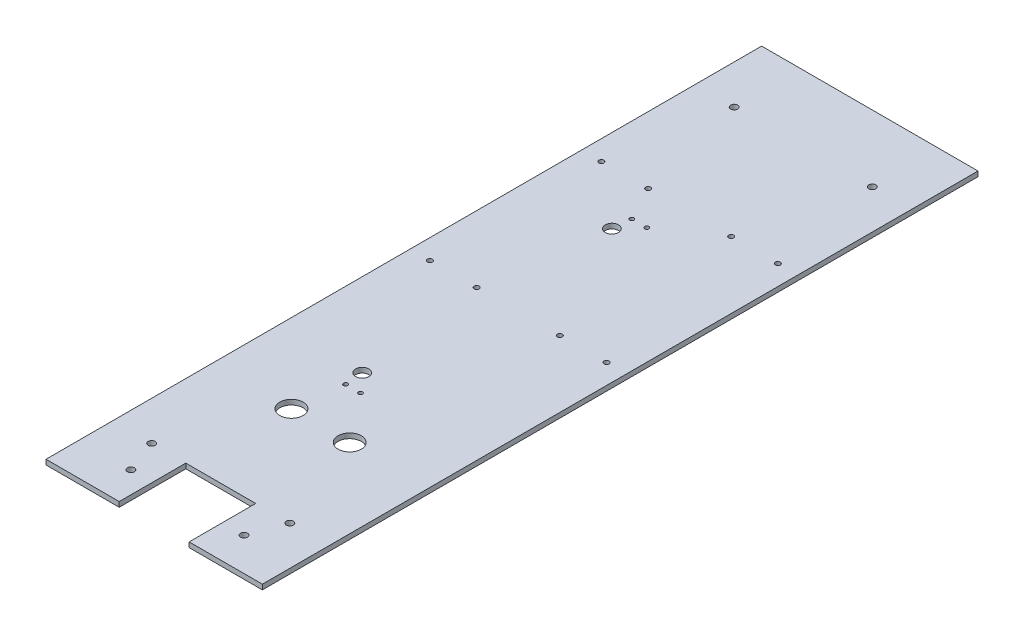
SolidWorks part; units mm, degrees
ref_plane "Front Plane" through (0, 0, 0) normal (0, 0, 1) x (1, 0, 0)
ref_plane "Top Plane" through (0, 0, 0) normal (0, 1, 0) x (1, 0, 0)
ref_plane "Right Plane" through (0, 0, 0) normal (1, 0, 0) x (0, 0, -1)
sketch "Sketch1" plane through (0, 0, 0) normal (0, 1, 0) x (1, 0, 0)
  line L1 (-65, 215) -> (65, 215)
  line L2 (-65, 215) -> (-65, -215)
  line L3 (-65, -215) -> (65, -215)
  line L4 (65, 215) -> (65, -215)
  line L5 (-65, 215) -> (65, -215) construction
  line L6 (-65, -215) -> (65, 215) construction
  point P0 (0, 0)
  dimension "D1" = 130
  dimension "D2" = 430
extrude "Boss-Extrude1" add sketch "Sketch1" along normal blind 3
sketch "Sketch2" plane through (0, 3, 0) normal (0, 1, 0) x (1, 0, 0)
  line L0 (-65, -215) -> (65, -215) construction
  line L1 (21, -215) -> (-21, -215)
  line L2 (21, -215) -> (21, -175)
  line L3 (21, -175) -> (-21, -175)
  line L4 (-21, -215) -> (-21, -175)
  line L5 (33, -180) -> (33, 215) construction
  line L6 (-33, -180) -> (-33, 215) construction
  dimension "D3" = 0
  dimension "D1" = 12
  dimension "D2" = 12
  dimension "D4" = 40
extrude "Cut-Extrude1" cut sketch "Sketch2" against normal blind 10 contours L2 L3 L4 L1
sketch "Sketch3" plane through (0, 0, 0) normal (0, -1, 0) x (1, 0, 0)
  line L0 (0, 33.6472) -> (0, -145.4342) construction
  line L1 (-65, -215) -> (-65, 215) construction
  line L2 (-65, 215) -> (-21, 215) construction
  line L3 (-65, -215) -> (-65, 215) construction
  line L4 (21, 215) -> (65, 215) construction
  line L5 (65, 215) -> (65, -215) construction
  circle A0 centre (-53.05, -3.75) radius 1.5
  circle A2 centre (-24.95, -3.75) radius 1.5
  circle A3 centre (-53.05, -106.75) radius 1.5
  circle A5 centre (-24.95, -106.75) radius 1.5
  circle A6 centre (24.95, -106.75) radius 1.5
  circle A7 centre (34, 195) radius 2.1
  circle A8 centre (53.05, -106.75) radius 1.5
  circle A9 centre (24.95, -3.75) radius 1.5
  circle A10 centre (-34, 195) radius 2.1
  circle A11 centre (53.05, -3.75) radius 1.5
  circle A12 centre (-41.5, 175) radius 2.1
  circle A13 centre (41.5, 175) radius 2.1
  circle A14 centre (41.5, -175) radius 2.1
  circle A15 centre (-41.5, -175) radius 2.1
  dimension "D1" = 3
  dimension "D3" = 20
  dimension "D4" = 4.2
  dimension "D5" = 4.2
  dimension "D6" = 31
  dimension "D7" = 20
  dimension "D8" = 31
  dimension "D2" = 65
extrude "Cut-Extrude2" cut sketch "Sketch3" against normal blind 10
sketch "Sketch4" plane through (0, 0, 0) normal (0, -1, 0) x (1, 0, 0)
  line L0 (-65, -215) -> (-65, 215) construction
  line L1 (-65, 215) -> (-21, 215) construction
  circle A0 centre (-17.5, 115) radius 7
  circle A1 centre (17.5, 115) radius 7
  dimension "D1" = 35
  dimension "D2" = 47.5
  dimension "D3" = 14
  dimension "D4" = 14
  dimension "D5" = 100
extrude "Cut-Extrude3" cut sketch "Sketch4" against normal blind 10
sketch "Sketch5" plane through (0, 0, 0) normal (0, -1, 0) x (1, 0, 0)
  line L0 (65, -215) -> (-65, -215) construction
  line L1 (-65, -215) -> (-65, 215) construction
  line L2 (-133.9447, 0) -> (168.7274, 0) construction
  circle A0 centre (-15, -75) radius 4
  circle A1 centre (-14, -86) radius 1.25
  circle A2 centre (-5, -86) radius 1.25
  circle A3 centre (-15, 75) radius 4
  circle A4 centre (-14, 86) radius 1.25
  circle A5 centre (-5, 86) radius 1.25
  dimension "D1" = 140
  dimension "D2" = 50
  dimension "D3" = 8
  dimension "D4" = 51
  dimension "D5" = 9
  dimension "D6" = 11
  dimension "D7" = 2.5
  dimension "D8" = 75
extrude "Cut-Extrude4" cut sketch "Sketch5" against normal blind 10
